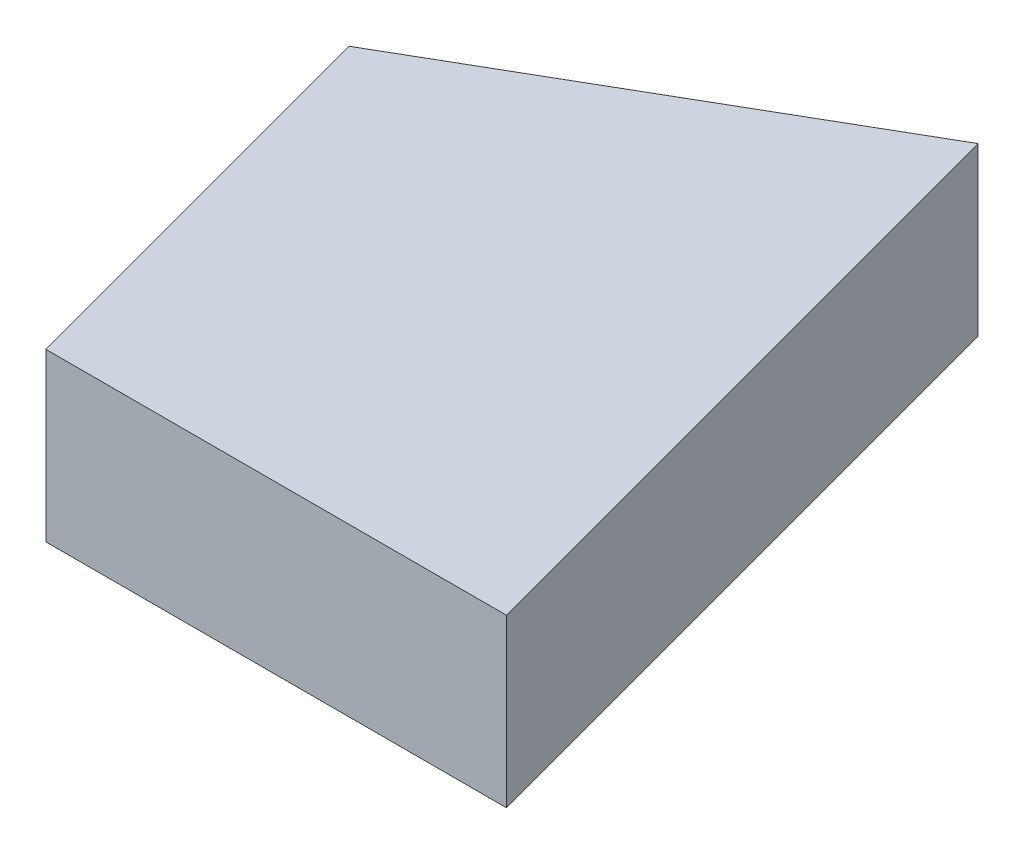
SolidWorks part; units mm, degrees
ref_plane "Front" through (0, 0, 0) normal (0, 0, 1) x (1, 0, 0)
ref_plane "Top" through (0, 0, 0) normal (0, 1, 0) x (1, 0, 0)
ref_plane "Right" through (0, 0, 0) normal (1, 0, 0) x (0, 0, -1)
sketch "Sketch1" plane through (0, 0, 0) normal (0, 1, 0) x (1, 0, 0)
  line L0 (0, 0) -> (94.6151, 0) construction
  line L1 (147.2071, 0) -> (127.4851, 73.6035)
  line L2 (127.4851, 73.6035) -> (73.6035, 127.4851) construction
  line L3 (73.6035, 127.4851) -> (0, 147.2071) construction
  line L4 (0, 147.2071) -> (-73.6035, 127.4851) construction
  line L5 (-73.6035, 127.4851) -> (-127.4851, 73.6035) construction
  line L6 (-127.4851, 73.6035) -> (-147.2071, 0) construction
  line L7 (-147.2071, 0) -> (-127.4851, -73.6035) construction
  line L8 (-127.4851, -73.6035) -> (-73.6035, -127.4851) construction
  line L9 (-73.6035, -127.4851) -> (0, -147.2071) construction
  line L10 (0, -147.2071) -> (73.6035, -127.4851) construction
  line L11 (73.6035, -127.4851) -> (127.4851, -73.6035) construction
  line L12 (127.4851, -73.6035) -> (147.2071, 0) construction
  line L13 (94.6151, 0) -> (81.9391, 47.3075)
  line L14 (81.9391, 47.3075) -> (47.3075, 81.9391) construction
  line L15 (47.3075, 81.9391) -> (0, 94.6151) construction
  line L16 (0, 94.6151) -> (-47.3075, 81.9391) construction
  line L17 (-47.3075, 81.9391) -> (-81.9391, 47.3075) construction
  line L18 (-81.9391, 47.3075) -> (-94.6151, 0) construction
  line L19 (-94.6151, 0) -> (-81.9391, -47.3075) construction
  line L20 (-81.9391, -47.3075) -> (-47.3075, -81.9391) construction
  line L21 (-47.3075, -81.9391) -> (0, -94.6151) construction
  line L22 (0, -94.6151) -> (47.3075, -81.9391) construction
  line L23 (47.3075, -81.9391) -> (81.9391, -47.3075) construction
  line L24 (81.9391, -47.3075) -> (94.6151, 0) construction
  line L25 (94.6151, 0) -> (147.2071, 0)
  line L26 (0, 0) -> (81.9391, 47.3075) construction
  line L27 (127.4851, 73.6035) -> (81.9391, 47.3075)
  line L28 (137.3461, 36.8018) -> (88.2771, 23.6538) construction
  circle A0 centre (0, 0) radius 142.1911 construction
  circle A1 centre (0, 0) radius 91.3911 construction
  dimension "width" = 50.8
  dimension "baselength" = 76.2
extrude "Boss-Extrude1" add sketch "Sketch1" along normal blind 19.05
